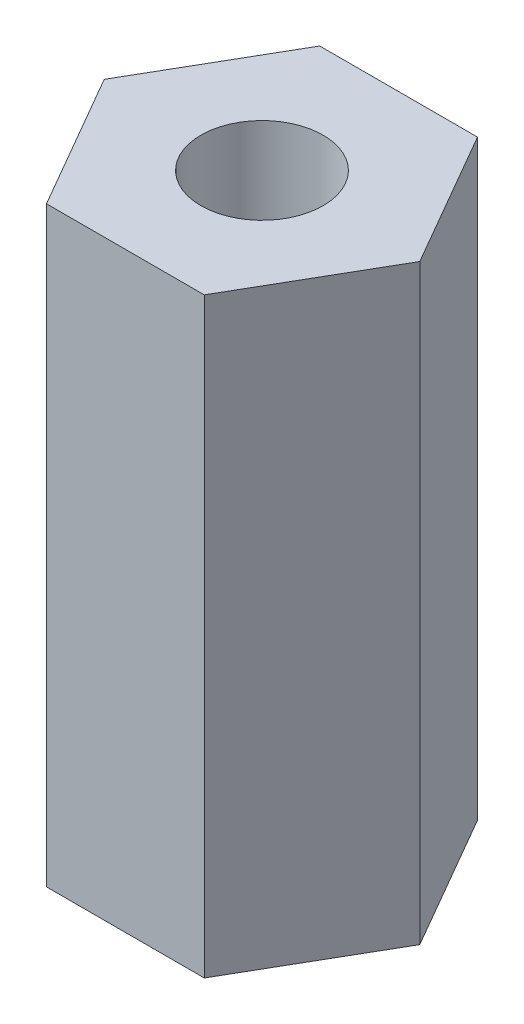
SolidWorks part; units mm, degrees
ref_plane "前基準面" through (0, 0, 0) normal (0, 0, 1) x (1, 0, 0)
ref_plane "上基準面" through (0, 0, 0) normal (0, 1, 0) x (1, 0, 0)
ref_plane "右基準面" through (0, 0, 0) normal (1, 0, 0) x (0, 0, -1)
sketch "草圖1" plane through (0, 0, 0) normal (0, 1, 0) x (1, 0, 0)
  line L1 (2, 3.4641) -> (-2, 3.4641)
  line L2 (-2, 3.4641) -> (-4, 0)
  line L3 (-4, 0) -> (-2, -3.4641)
  line L4 (-2, -3.4641) -> (2, -3.4641)
  line L5 (2, -3.4641) -> (4, 0)
  line L6 (4, 0) -> (2, 3.4641)
  circle A0 centre (0, 0) radius 3.4641 construction
  circle A1 centre (0, 0) radius 1.55
  dimension "D1" = 3.1
  dimension "D2" = 4
extrude "填料-伸長1" add sketch "草圖1" along normal blind 15 contours A1 | L1 L2 L3 L4 L5 L6
